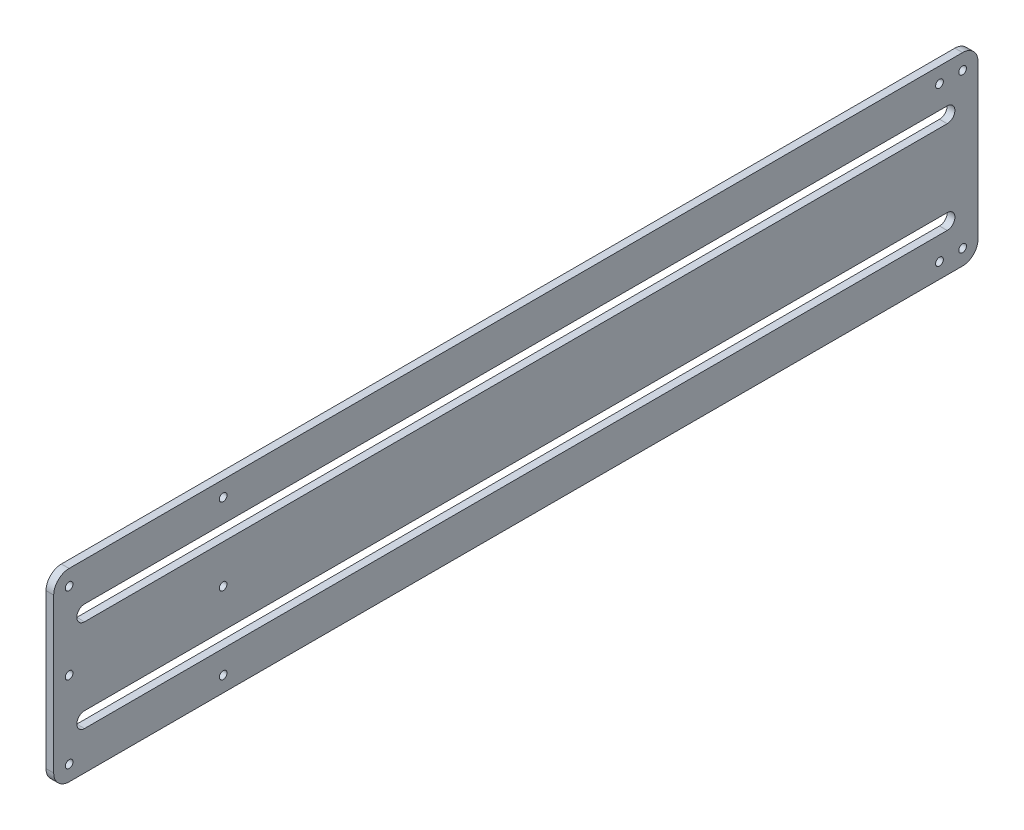
SolidWorks part; units mm, degrees
ref_plane "Front Plane" through (0, 0, 0) normal (0, 0, 1) x (1, 0, 0)
ref_plane "Top Plane" through (0, 0, 0) normal (0, 1, 0) x (1, 0, 0)
ref_plane "Right Plane" through (0, 0, 0) normal (1, 0, 0) x (0, 0, -1)
sketch "Sketch1" plane through (0, 0, 0) normal (1, 0, 0) x (0, 0, -1)
  line L1 (-184.15, -38.1) -> (184.15, -38.1)
  line L2 (-190.5, -31.75) -> (-190.5, 31.75)
  line L3 (-184.15, 38.1) -> (184.15, 38.1)
  line L4 (190.5, -31.75) -> (190.5, 31.75)
  line L5 (-190.5, -38.1) -> (190.5, 38.1) construction
  line L6 (-190.5, 38.1) -> (190.5, -38.1) construction
  arc A0 (-190.5, -31.75) -> (-184.15, -38.1) centre (-184.15, -31.75) ccw
  arc A1 (184.15, -38.1) -> (190.5, -31.75) centre (184.15, -31.75) ccw
  arc A2 (190.5, 31.75) -> (184.15, 38.1) centre (184.15, 31.75) ccw
  arc A3 (-184.15, 38.1) -> (-190.5, 31.75) centre (-184.15, 31.75) ccw
  point P0 (0, 0)
  dimension "D3" = 6.35
  dimension "D1" = 381
  dimension "D2" = 76.2
extrude "Outer Cut" add sketch "Sketch1" along normal mid plane 3.175
sketch "Sketch2" plane through (1.5875, 0, 0) normal (1, 0, 0) x (0, 0, -1)
  line L0 (-177.8, 19.05) -> (177.8, 19.05) construction
  line L1 (-177.8, 22.225) -> (177.8, 22.225)
  line L2 (-177.8, 15.875) -> (177.8, 15.875)
  line L3 (-190.5, 0) -> (190.5, 0) construction
  line L6 (190.5, -31.75) -> (190.5, 31.75) construction
  line L7 (-190.5, 31.75) -> (-190.5, -31.75) construction
  line L8 (-177.8, -19.05) -> (177.8, -19.05) construction
  line L9 (-177.8, -22.225) -> (177.8, -22.225)
  line L10 (-177.8, -15.875) -> (177.8, -15.875)
  arc A0 (-177.8, 22.225) -> (-177.8, 15.875) centre (-177.8, 19.05) ccw
  arc A1 (177.8, 15.875) -> (177.8, 22.225) centre (177.8, 19.05) ccw
  arc A2 (-177.8, -22.225) -> (-177.8, -15.875) centre (-177.8, -19.05) cw
  arc A3 (177.8, -15.875) -> (177.8, -22.225) centre (177.8, -19.05) cw
  point P2 (0, 19.05)
  point P18 (0, -19.05)
  dimension "D1" = 6.35
  dimension "D2" = 38.1
  dimension "D3" = 12.7
  dimension "D4" = 12.7
extrude "Slots" cut sketch "Sketch2" against normal through all
sketch "Sketch3" plane through (1.5875, 0, 0) normal (1, 0, 0) x (0, 0, -1)
  line L0 (-184.15, 31.75) -> (-120.65, 31.75) construction
  line L1 (184.15, 38.1) -> (-184.15, 38.1) construction
  line L2 (-190.5, 31.75) -> (-190.5, -31.75) construction
  line L3 (0, 0) -> (-190.5, 0) construction
  circle A0 centre (-184.15, 31.75) radius 1.5875
  circle A1 centre (-120.65, 31.75) radius 1.5875
  circle A2 centre (-120.65, -31.75) radius 1.5875
  circle A3 centre (-184.15, -31.75) radius 1.5875
  circle A4 centre (-184.15, 0) radius 1.5875
  circle A5 centre (-120.65, 0) radius 1.5875
  dimension "D1" = 3.175
  dimension "D3" = 63.5
  dimension "D4" = 6.35
  dimension "D5" = 6.35
extrude "Mount Holes" cut sketch "Sketch3" against normal through all
sketch "Sketch4" plane through (1.5875, 0, 0) normal (1, 0, 0) x (0, 0, -1)
  line L0 (190.5, -31.75) -> (190.5, 31.75) construction
  line L1 (184.15, 38.1) -> (-184.15, 38.1) construction
  line L2 (0, 0) -> (190.5, 0) construction
  circle A0 centre (184.15, 31.75) radius 1.5875
  circle A2 centre (174.625, 31.75) radius 1.5875
  circle A3 centre (174.625, -31.75) radius 1.5875
  circle A4 centre (184.15, -31.75) radius 1.5875
  dimension "D3" = 3.175
  dimension "D1" = 6.35
  dimension "D2" = 6.35
  dimension "D5" = 9.525
  dimension "D4" = 2
extrude "Cut-Extrude1" cut sketch "Sketch4" against normal through all
